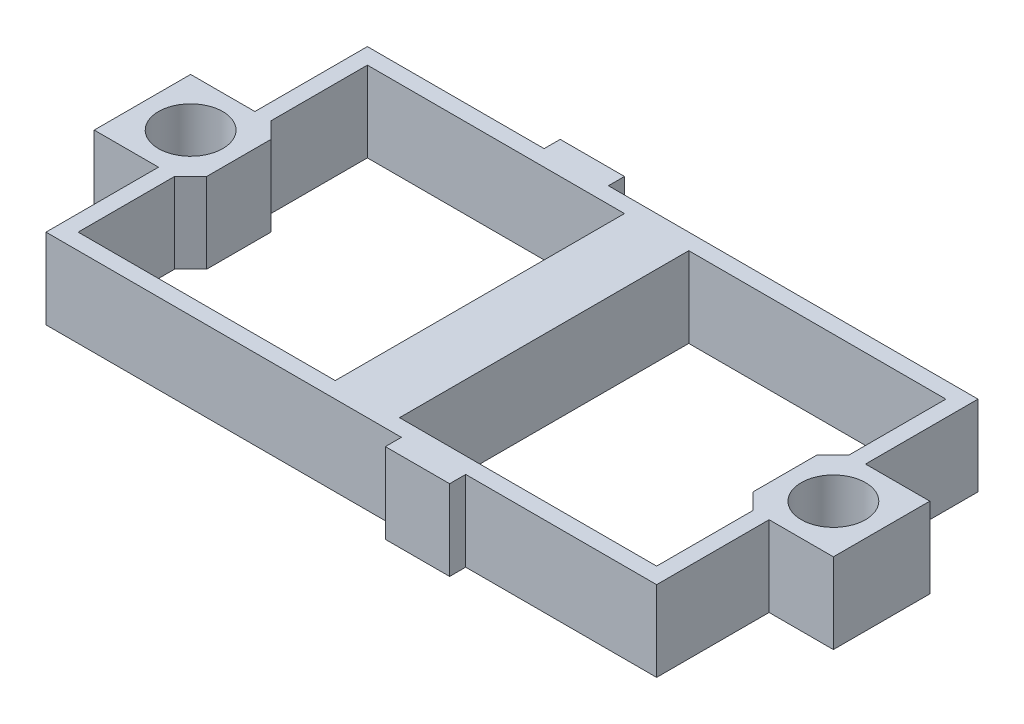
SolidWorks part; units mm, degrees
ref_plane "Front Plane" through (0, 0, 0) normal (0, 0, 1) x (1, 0, 0)
ref_plane "Top Plane" through (0, 0, 0) normal (0, 1, 0) x (1, 0, 0)
ref_plane "Right Plane" through (0, 0, 0) normal (1, 0, 0) x (0, 0, -1)
sketch "Sketch1" plane through (0, 0, 0) normal (0, 1, 0) x (1, 0, 0)
  line L0 (0, 127) -> (69.85, 127)
  line L5 (241.3, 0) -> (165.8517, 0)
  line L7 (69.85, 127) -> (69.85, 133.35)
  line L8 (69.85, 133.35) -> (95.25, 133.35)
  line L9 (95.25, 127) -> (95.25, 133.35)
  line L10 (0, 127) -> (0, 82.55)
  line L12 (165.8517, 0) -> (165.8517, -6.35)
  line L13 (165.8517, -6.35) -> (140.4517, -6.35)
  line L14 (140.4517, 0) -> (140.4517, -6.35)
  line L15 (0, 82.55) -> (-25.4, 82.55)
  line L17 (0, 44.45) -> (-25.4, 44.45)
  line L18 (-25.4, 82.55) -> (-25.4, 44.45)
  line L19 (241.3, 82.55) -> (266.7, 82.55)
  line L21 (241.3, 44.45) -> (266.7, 44.45)
  line L22 (266.7, 82.55) -> (266.7, 44.45)
  line L23 (0, 44.45) -> (0, 0)
  line L24 (241.3, 127) -> (241.3, 82.55)
  line L25 (241.3, 44.45) -> (241.3, 0)
  line L26 (140.4517, 0) -> (140.4517, -6.35)
  line L27 (165.8517, -6.35) -> (165.8517, 0)
  line L28 (0, 0) -> (140.4517, 0)
  line L29 (95.25, 127) -> (241.3, 127)
  line L30 (107.95, 6.35) -> (107.95, 120.65)
  line L31 (107.95, 6.35) -> (6.35, 6.35)
  line L32 (107.95, 120.65) -> (6.35, 120.65)
  line L33 (6.35, 6.35) -> (6.35, 44.45)
  line L34 (6.35, 120.65) -> (6.35, 82.55)
  line L37 (6.35, 44.45) -> (12.7, 50.8)
  line L38 (12.7, 50.8) -> (12.7, 76.2)
  line L39 (133.35, 120.65) -> (133.35, 6.35)
  line L40 (133.35, 120.65) -> (234.95, 120.65)
  line L41 (6.35, 82.55) -> (12.7, 76.2)
  line L42 (133.35, 6.35) -> (234.95, 6.35)
  line L43 (234.95, 6.35) -> (234.95, 44.45)
  line L44 (234.95, 120.65) -> (234.95, 82.55)
  line L49 (234.95, 82.55) -> (228.6, 76.2)
  line L50 (228.6, 50.8) -> (234.95, 44.45)
  line L51 (228.6, 76.2) -> (228.6, 50.8)
  circle A1 centre (-6.35, 63.5) radius 12.7
  circle A3 centre (247.65, 63.5) radius 12.7
  point P17 (-25.4, 63.5)
  point P24 (266.7, 63.5)
  dimension "D10" = 6.35
  dimension "D15" = 6.35
  dimension "D16" = 25.4
  dimension "D1" = 241.3
  dimension "D2" = 127
  dimension "D3" = 6.35
  dimension "D4" = 25.4
  dimension "D5" = 6.35
  dimension "D6" = 25.4
  dimension "D7" = 25.4
  dimension "D8" = 63.5
  dimension "D9" = 38.1
  dimension "D11" = 19.05
  dimension "D12" = 25.4
  dimension "D13" = 63.5
  dimension "D14" = 38.1
  dimension "D17" = 6.35
  dimension "D18" = 6.35
  dimension "D19" = 101.6
  dimension "D20" = 6.35
  dimension "D21" = 6.35
  dimension "D22" = 114.3
  dimension "D23" = 25.4
  dimension "D24" = 25.4
  dimension "D25" = 101.6
extrude "Boss-Extrude2" add sketch "Sketch1" along normal blind 31.75 contours L29 L9 L8 L7 L0 L10 L15 L18 L17 L23 L28 L14 L13 L12 L5 L25 L21 L22 L19 L24 A3 A1 L41 L34 L32 L30 L31 L33 L37 L38 L49 L51 L50 L43 L42 L39 L40 L44
